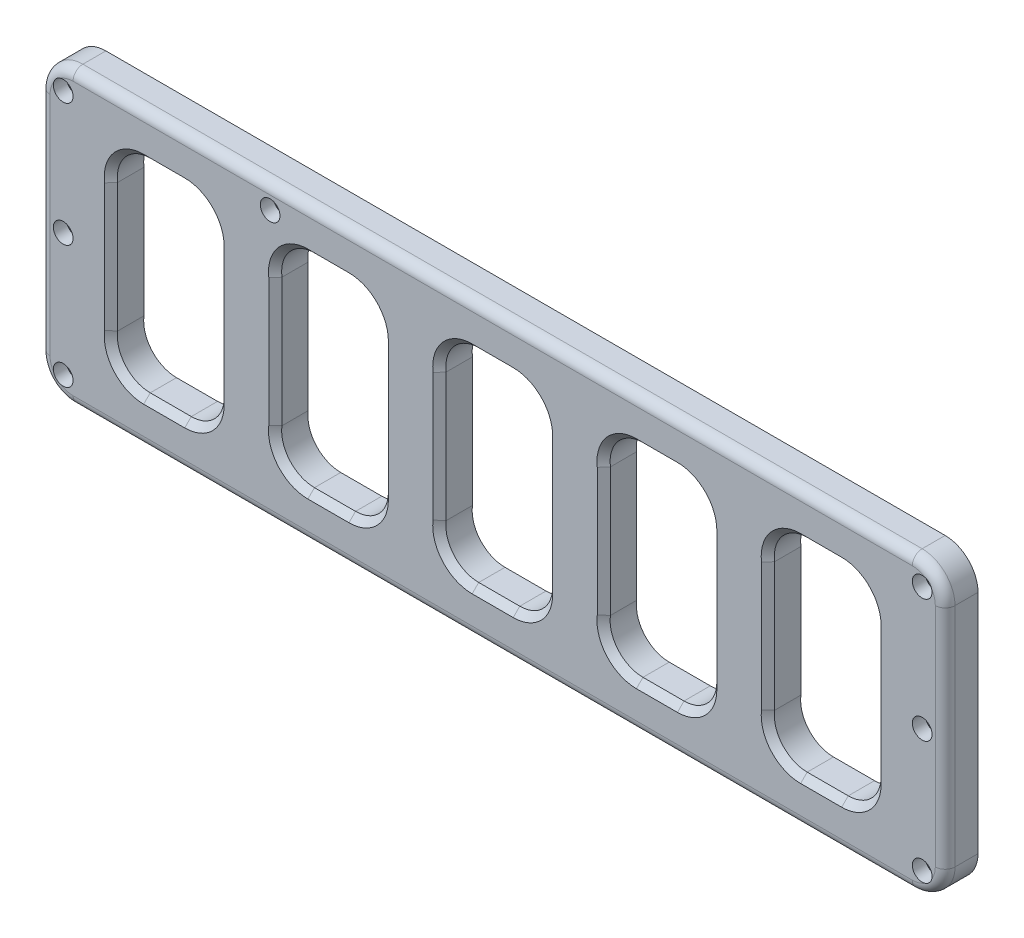
SolidWorks part; units mm, degrees
ref_plane "前视基准面" through (0, 0, 0) normal (0, 0, 1) x (1, 0, 0)
ref_plane "上视基准面" through (0, 0, 0) normal (0, 1, 0) x (1, 0, 0)
ref_plane "右视基准面" through (0, 0, 0) normal (1, 0, 0) x (0, 0, -1)
other "Configuration Table"
sketch "草图1" plane through (0, 0, 0) normal (0, 0, 1) x (1, 0, 0)
  line L1 (-137.75, -44.45) -> (137.75, -44.45)
  line L2 (-137.75, -44.45) -> (-137.75, 44.45)
  line L3 (-137.75, 44.45) -> (137.75, 44.45)
  line L4 (137.75, -44.45) -> (137.75, 44.45)
  line L5 (-137.75, -44.45) -> (137.75, 44.45) construction
  line L6 (-137.75, 44.45) -> (137.75, -44.45) construction
  point P0 (0, 0)
extrude "凸台-拉伸1" add sketch "草图1" along normal blind 10
fillet "圆角1" radius 10 4 edges at (-137.75, -44.45, 5) (137.75, -44.45, 5) (137.75, 44.45, 5) (-137.75, 44.45, 5)
sketch "草图2" plane through (0, 0, 10) normal (0, 0, 1) x (1, 0, 0)
  line L2 (-127.75, -30.95) -> (-127.75, 30.95) construction
  line L4 (127.75, -30.95) -> (127.75, 30.95) construction
  line L5 (-127.75, -30.95) -> (127.75, 30.95) construction
  line L6 (-127.75, 30.95) -> (127.75, -30.95) construction
  line L9 (-6.25, 30.95) -> (6.25, 30.95)
  line L10 (16.25, 20.95) -> (16.25, -20.95)
  line L15 (-43.75, -30.95) -> (-56.25, -30.95)
  line L16 (-66.1565, -19.5859) -> (-66.1565, 19.5859)
  line L21 (56.25, -30.95) -> (43.75, -30.95)
  line L22 (33.8435, -19.5859) -> (33.8435, 19.5859)
  line L38 (6.25, -20.95) -> (-6.25, -20.95) construction
  line L39 (-6.25, 30.95) -> (-6.25, 20.95) construction
  line L40 (6.25, -20.95) -> (6.25, 20.95) construction
  line L41 (6.25, 30.95) -> (6.25, 20.95) construction
  line L42 (6.25, 20.95) -> (-6.25, 20.95) construction
  line L43 (-6.25, -20.95) -> (-6.25, 20.95) construction
  line L44 (6.25, -20.95) -> (-6.25, 20.95) construction
  line L45 (6.25, -30.95) -> (6.25, -20.95) construction
  line L46 (6.25, -30.95) -> (-6.25, -30.95)
  line L47 (-16.1565, -19.5859) -> (-16.1565, 19.5859)
  line L48 (6.25, 20.95) -> (-6.25, -20.95) construction
  line L49 (43.75, 30.95) -> (56.25, 30.95)
  line L50 (66.25, 20.95) -> (66.25, -20.95)
  line L51 (106.25, -30.95) -> (93.75, -30.95)
  line L52 (83.8435, -19.5859) -> (83.8435, 19.5859)
  line L53 (93.75, 30.95) -> (106.25, 30.95)
  line L54 (116.25, 20.95) -> (116.25, -20.95)
  line L55 (-56.25, 30.95) -> (-43.75, 30.95)
  line L56 (-33.75, 20.95) -> (-33.75, -20.95)
  line L57 (-93.75, -30.95) -> (-106.25, -30.95)
  line L58 (-116.1565, -19.5859) -> (-116.1565, 19.5859)
  line L59 (-106.25, 30.95) -> (-93.75, 30.95)
  line L60 (-83.75, 20.95) -> (-83.75, -20.95)
  arc A0 (-6.25, -30.95) -> (-16.1565, -19.5859) centre (-6.25, -20.95) cw
  arc A1 (6.25, -30.95) -> (16.25, -20.95) centre (6.25, -20.95) ccw
  arc A2 (16.25, 20.95) -> (6.25, 30.95) centre (6.25, 20.95) ccw
  arc A3 (-6.25, 30.95) -> (-16.1565, 19.5859) centre (-6.25, 20.95) ccw
  arc A4 (56.25, -30.95) -> (66.25, -20.95) centre (56.25, -20.95) ccw
  arc A5 (43.75, -30.95) -> (33.8435, -19.5859) centre (43.75, -20.95) cw
  arc A6 (43.75, 30.95) -> (33.8435, 19.5859) centre (43.75, 20.95) ccw
  arc A7 (66.25, 20.95) -> (56.25, 30.95) centre (56.25, 20.95) ccw
  arc A8 (106.25, -30.95) -> (116.25, -20.95) centre (106.25, -20.95) ccw
  arc A9 (93.75, -30.95) -> (83.8435, -19.5859) centre (93.75, -20.95) cw
  arc A10 (93.75, 30.95) -> (83.8435, 19.5859) centre (93.75, 20.95) ccw
  arc A11 (116.25, 20.95) -> (106.25, 30.95) centre (106.25, 20.95) ccw
  arc A12 (-43.75, -30.95) -> (-33.75, -20.95) centre (-43.75, -20.95) ccw
  arc A13 (-56.25, -30.95) -> (-66.1565, -19.5859) centre (-56.25, -20.95) cw
  arc A14 (-56.25, 30.95) -> (-66.1565, 19.5859) centre (-56.25, 20.95) ccw
  arc A15 (-33.75, 20.95) -> (-43.75, 30.95) centre (-43.75, 20.95) ccw
  arc A16 (-93.75, -30.95) -> (-83.75, -20.95) centre (-93.75, -20.95) ccw
  arc A17 (-106.25, -30.95) -> (-116.1565, -19.5859) centre (-106.25, -20.95) cw
  arc A18 (-106.25, 30.95) -> (-116.1565, 19.5859) centre (-106.25, 20.95) ccw
  arc A19 (-83.75, 20.95) -> (-93.75, 30.95) centre (-93.75, 20.95) ccw
  point P0 (0, 0)
  point P6 (0, 0)
  point P11 (0, 0)
  point P12 (0, 0)
  dimension "D2" = 10
  dimension "D3" = 10
  dimension "D5" = 10
  dimension "D6" = 10
  dimension "D1" = 12.5
  dimension "D4" = 255.5
  dimension "D7" = 61.9
  dimension "D8" = 3
  dimension "D9" = 3
extrude "切除-拉伸1" cut sketch "草图2" against normal blind 10
chamfer "倒角2" distance 2 angle 45 40 edges at (113.3211, -28.0211, 10) (100, -30.95, 10) (86.212, -27.5211, 10) (116.25, 0, 10) (83.8435, 0, 10) (113.3211, 28.0211, 10) (86.212, 27.5211, 10) (100, 30.95, 10) (63.3211, -28.0211, 10) (50, -30.95, 10) (36.212, -27.5211, 10) (66.25, 0, 10) (33.8435, 0, 10) (63.3211, 28.0211, 10) (50, 30.95, 10) (36.212, 27.5211, 10) (13.3211, -28.0211, 10) (0, -30.95, 10) (-13.788, -27.5211, 10) (16.25, 0, 10) (-16.1565, 0, 10) (13.3211, 28.0211, 10) (0, 30.95, 10) (-13.788, 27.5211, 10) (-36.6789, -28.0211, 10) (-50, -30.95, 10) (-63.788, -27.5211, 10) (-33.75, 0, 10) (-66.1565, 0, 10) (-36.6789, 28.0211, 10) (-50, 30.95, 10) (-63.788, 27.5211, 10) (-86.6789, -28.0211, 10) (-100, -30.95, 10) (-113.788, -27.5211, 10) (-83.75, 0, 10) (-116.1565, 0, 10) (-86.6789, 28.0211, 10) (-100, 30.95, 10) (-113.788, 27.5211, 10)
fillet "圆角3" radius 3 8 edges at (-134.8211, -41.5211, 10) (0, -44.45, 10) (134.8211, -41.5211, 10) (137.75, 0, 10) (134.8211, 41.5211, 10) (-137.75, 0, 10) (0, 44.45, 10) (-134.8211, 41.5211, 10)
sketch "草图3" plane through (0, 0, 0) normal (0, 0, -1) x (-1, 0, 0)
  line L0 (-137.75, -34.45) -> (-137.75, 34.45) construction
  line L1 (-127.75, -41.95) -> (127.75, -41.95)
  line L2 (-127.75, -41.95) -> (-127.75, -38.95)
  line L3 (-127.75, -38.95) -> (127.75, -38.95)
  line L4 (127.75, -41.95) -> (127.75, -38.95)
  line L5 (127.75, -44.45) -> (-127.75, -44.45) construction
  line L6 (137.75, 34.45) -> (137.75, -34.45) construction
  dimension "D1" = 10
  dimension "D2" = 2.5
  dimension "D3" = 3
  dimension "D4" = 10
extrude "切除-拉伸2" cut sketch "草图3" against normal blind 4
sketch "草图4" plane through (0, 0, 0) normal (0, 0, -1) x (-1, 0, 0)
  line L0 (-137.75, -34.45) -> (-137.75, 34.45) construction
  line L1 (127.75, -44.45) -> (-127.75, -44.45) construction
  line L2 (137.75, 34.45) -> (137.75, -34.45) construction
  line L3 (-127.75, 44.45) -> (127.75, 44.45) construction
  line L4 (-130.75, 37.45) -> (-130.75, -37.45) construction
  line L5 (130.75, 37.45) -> (130.75, -37.45) construction
  circle A0 centre (-130.75, 37.45) radius 1.5
  circle A1 centre (130.75, 37.45) radius 1.5
  circle A2 centre (130.75, -37.45) radius 1.5
  circle A3 centre (-130.75, -37.45) radius 1.5
  circle A4 centre (67.75, 37.45) radius 1.5
  circle A5 centre (-130.75, 0) radius 1.5
  circle A6 centre (130.75, 0) radius 1.5
  dimension "D1" = 7
  dimension "D2" = 7
  dimension "D5" = 70
  dimension "D3" = 7
  dimension "D4" = 7
extrude "切除-拉伸3" cut sketch "草图4" against normal blind 46
sketch "草图5" plane through (0, 0, 10) normal (0, 0, 1) x (1, 0, 0)
  circle A4 centre (-67.75, 37.45) radius 1.5 construction
  circle A5 centre (-67.75, 37.45) radius 1.5
  circle A7 centre (130.75, 0) radius 1.5 construction
  circle A8 centre (-130.75, 0) radius 1.5 construction
  circle A9 centre (130.75, 0) radius 1.5
  circle A10 centre (-130.75, 0) radius 1.5
  circle A13 centre (-130.75, 37.45) radius 1.5 construction
  circle A14 centre (-130.75, 37.45) radius 1.5
  circle A15 centre (-130.75, -37.45) radius 1.5 construction
  circle A16 centre (-130.75, -37.45) radius 1.5
  circle A17 centre (130.75, 37.45) radius 1.5 construction
  circle A18 centre (130.75, 37.45) radius 1.5
  circle A19 centre (130.75, -37.45) radius 1.5 construction
  circle A20 centre (130.75, -37.45) radius 1.5
  circle A21 centre (-67.75, 37.45) radius 3
  circle A22 centre (130.75, 0) radius 3
  circle A23 centre (-130.75, 0) radius 3
  circle A24 centre (-130.75, 37.45) radius 3
  circle A25 centre (-130.75, -37.45) radius 3
  circle A26 centre (130.75, 37.45) radius 3
  circle A27 centre (130.75, -37.45) radius 3
  dimension "D1" = 1.5
extrude "切除-拉伸4" cut sketch "草图5" against normal blind 4
sketch "草图6" plane through (0, 0, 0) normal (0, 0, -1) x (-1, 0, 0)
  line L0 (-137.75, -34.45) -> (-137.75, 34.45) construction
  line L1 (-77.75, 37.95) -> (57.75, 37.95)
  line L2 (-77.75, 37.95) -> (-77.75, 40.95)
  line L3 (-77.75, 40.95) -> (57.75, 40.95)
  line L4 (57.75, 37.95) -> (57.75, 40.95)
  line L5 (137.75, 34.45) -> (137.75, -34.45) construction
  line L6 (-127.75, 44.45) -> (127.75, 44.45) construction
  dimension "D1" = 60
  dimension "D2" = 80
  dimension "D3" = 3.5
  dimension "D4" = 3
extrude "凸台-拉伸2" add sketch "草图6" along normal blind 3
